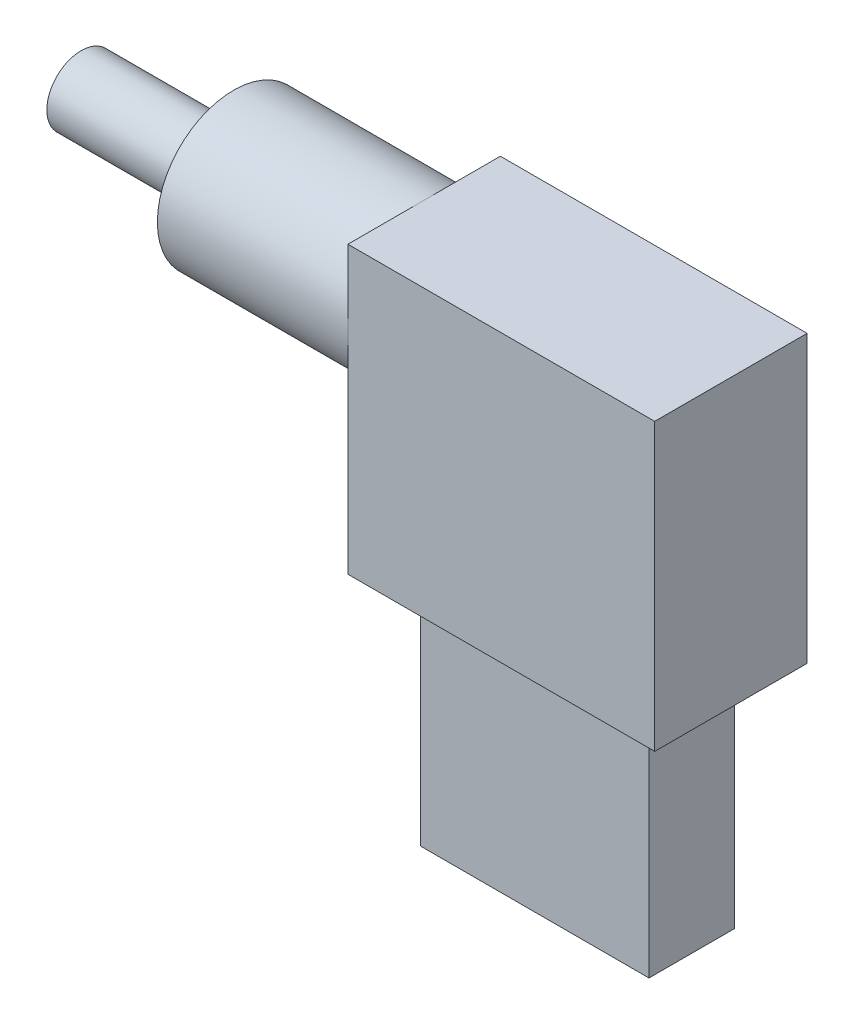
SolidWorks part; units mm, degrees
ref_plane "Plan de face" through (0, 0, 0) normal (0, 0, 1) x (1, 0, 0)
ref_plane "Plan de dessus" through (0, 0, 0) normal (0, 1, 0) x (1, 0, 0)
ref_plane "Plan de droite" through (0, 0, 0) normal (1, 0, 0) x (0, 0, -1)
sketch "Esquisse1" plane through (0, 0, 0) normal (0, 1, 0) x (1, 0, 0)
  line L0 (-5.7, 1.95) -> (-5.7, -1.95)
  line L1 (-6, 2.25) -> (6, 2.25)
  line L2 (-6, 2.25) -> (-6, -2.25)
  line L3 (-6, -2.25) -> (6, -2.25)
  line L4 (6, 2.25) -> (6, -2.25)
  line L9 (-5.7, -1.95) -> (5.7, -1.95)
  line L10 (5.7, 1.95) -> (5.7, -1.95)
  line L11 (-5.7, 1.95) -> (5.7, 1.95)
  line L12 (-5.7, 0.05) -> (5.7, 0.05)
  point P4 (0, 2.25)
  point P6 (-6, 0)
  dimension "D1" = 12
  dimension "D2" = 4.5
  dimension "D4" = 2.3
  dimension "D3" = 0.3
extrude "Boss.-Extru.1" add sketch "Esquisse1" along normal blind 12.2 contours L4 L1 L2 L3 L0 L11 L10 L9 | L12 L0 L9 L10
sketch "Esquisse2" plane through (0, 12.2, 0) normal (0, 1, 0) x (1, 0, 0)
  line L1 (-8.05, 4) -> (8.05, 4)
  line L2 (-8.05, 4) -> (-8.05, -4)
  line L3 (-8.05, -4) -> (8.05, -4)
  line L4 (8.05, 4) -> (8.05, -4)
  point P4 (8.6349, -3.2473)
  point P6 (0, 4)
  point P7 (-8.05, 0)
  dimension "D1" = 16.1
  dimension "D2" = 8
extrude "Boss.-Extru.2" add sketch "Esquisse2" along normal blind 15
sketch "Esquisse3" plane through (-8.05, 0, 0) normal (-1, 0, 0) x (0, 0, 1)
  line L0 (-4, 27.2) -> (4, 27.2) construction
  line L3 (4, 27.2) -> (4, 12.2) construction
  circle A0 centre (0, 23.2) radius 4
  point P2 (0, 0)
extrude "Boss.-Extru.3" add sketch "Esquisse3" along normal blind 10
sketch "Esquisse4" plane through (-18.05, 0, 0) normal (-1, 0, 0) x (0, 0, 1)
  circle A0 centre (0, 23.2) radius 1.8
  dimension "D1" = 3.6
extrude "Boss.-Extru.4" add sketch "Esquisse4" along normal blind 8
